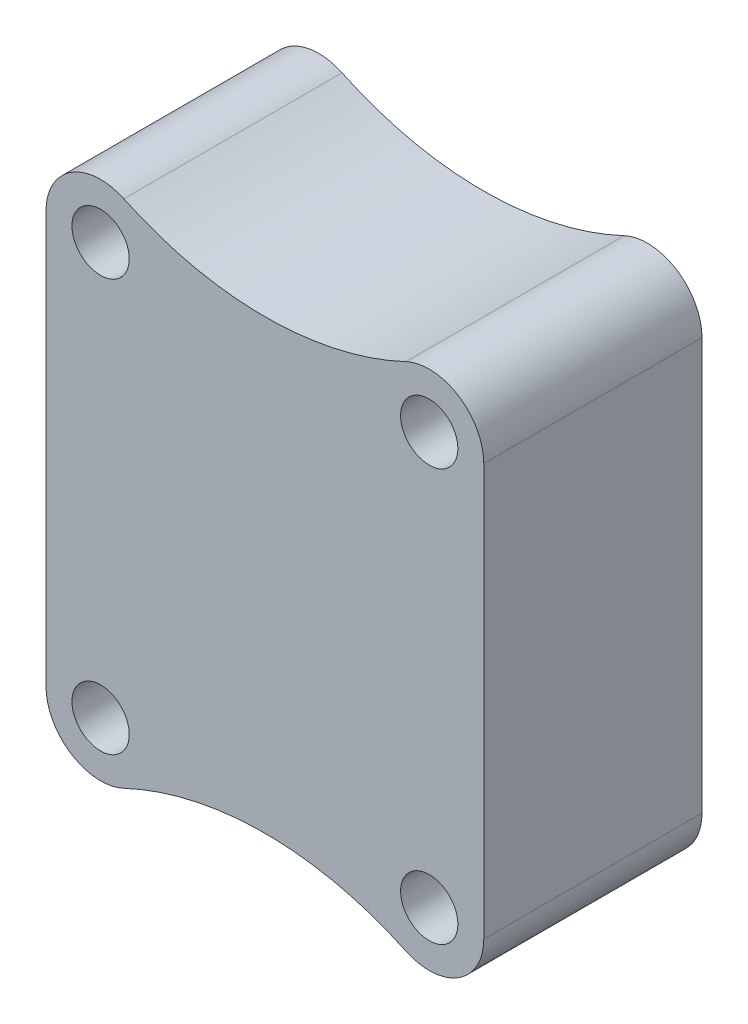
SolidWorks part; units mm, degrees
ref_plane "Front Plane" through (0, 0, 0) normal (0, 0, 1) x (1, 0, 0)
ref_plane "Top Plane" through (0, 0, 0) normal (0, 1, 0) x (1, 0, 0)
ref_plane "Right Plane" through (0, 0, 0) normal (1, 0, 0) x (0, 0, -1)
sketch "Sketch1" plane through (0, 0, 0) normal (0, 0, 1) x (1, 0, 0)
  line L0 (24.1, 30.2) -> (24.1, 0) construction
  line L2 (-4, 0) -> (-4, 30.2)
  line L4 (28.1, 0) -> (28.1, 30.2)
  line L5 (24.1, 30.2) -> (0, 30.2) construction
  line L6 (0, 30.2) -> (0, 0) construction
  line L8 (24.1, 0) -> (0, 0) construction
  arc A0 (1.7068, -3.6176) -> (-4, 0) centre (0, 0) cw
  arc A1 (22.3932, -3.6176) -> (28.1, 0) centre (24.1, 0) ccw
  arc A2 (22.3932, 33.8176) -> (28.1, 30.2) centre (24.1, 30.2) cw
  arc A3 (-4, 30.2) -> (1.7068, 33.8176) centre (0, 30.2) cw
  circle A4 centre (0, 0) radius 2.1
  circle A5 centre (0, 30.2) radius 2.1
  circle A6 centre (24.1, 30.2) radius 2.1
  circle A7 centre (24.1, 0) radius 2.1
  arc A8 (22.3932, 33.8176) -> (1.7068, 33.8176) centre (12.05, 55.7394) cw
  arc A9 (22.3932, -3.6176) -> (1.7068, -3.6176) centre (12.05, -25.5394) ccw
  point P7 (0, 0)
  point P20 (0, 0)
  point P21 (0, 0)
  dimension "D1" = 26
  dimension "D3" = 4.2
  dimension "D4" = 19.9
  dimension "D5" = 46.6374
  dimension "D6" = 32.8
  dimension "D7" = 38.2
  dimension "D8" = 19.9
  dimension "D2" = 32.1
extrude "Boss-Extrude1" add sketch "Sketch1" along normal blind 16
